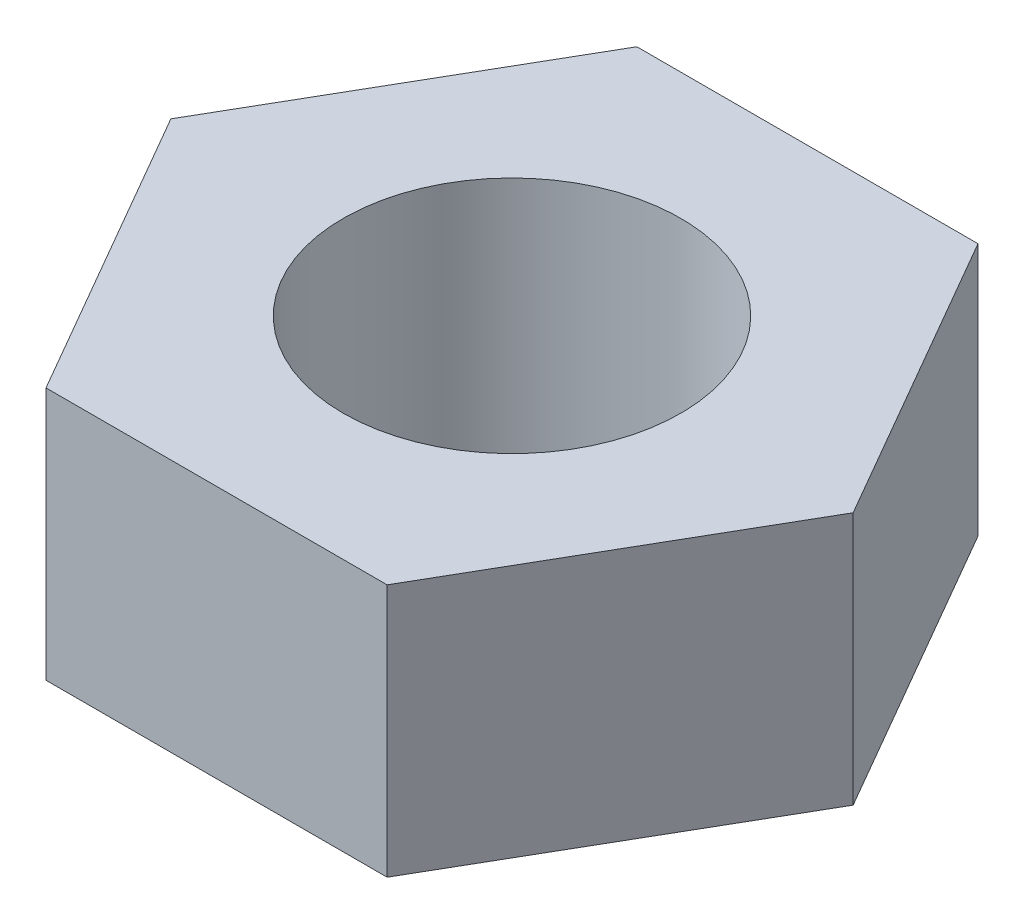
SolidWorks part; units mm, degrees
ref_plane "前视基准面" through (0, 0, 0) normal (0, 0, 1) x (1, 0, 0)
ref_plane "上视基准面" through (0, 0, 0) normal (0, 1, 0) x (1, 0, 0)
ref_plane "右视基准面" through (0, 0, 0) normal (1, 0, 0) x (0, 0, -1)
other "Configuration Table"
sketch "Sketch1" plane through (0, 0, 0) normal (0, 1, 0) x (1, 0, 0)
  line L1 (4.0415, 0) -> (2.0207, 3.5)
  line L2 (2.0207, 3.5) -> (-2.0207, 3.5)
  line L3 (-2.0207, 3.5) -> (-4.0415, 0)
  line L4 (-4.0415, 0) -> (-2.0207, -3.5)
  line L5 (-2.0207, -3.5) -> (2.0207, -3.5)
  line L6 (2.0207, -3.5) -> (4.0415, 0)
  circle A0 centre (0, 0) radius 3.5 construction
  circle A1 centre (0, 0) radius 2
  dimension "D1" = 7
extrude "Boss-Extrude1" add sketch "Sketch1" along normal blind 3
